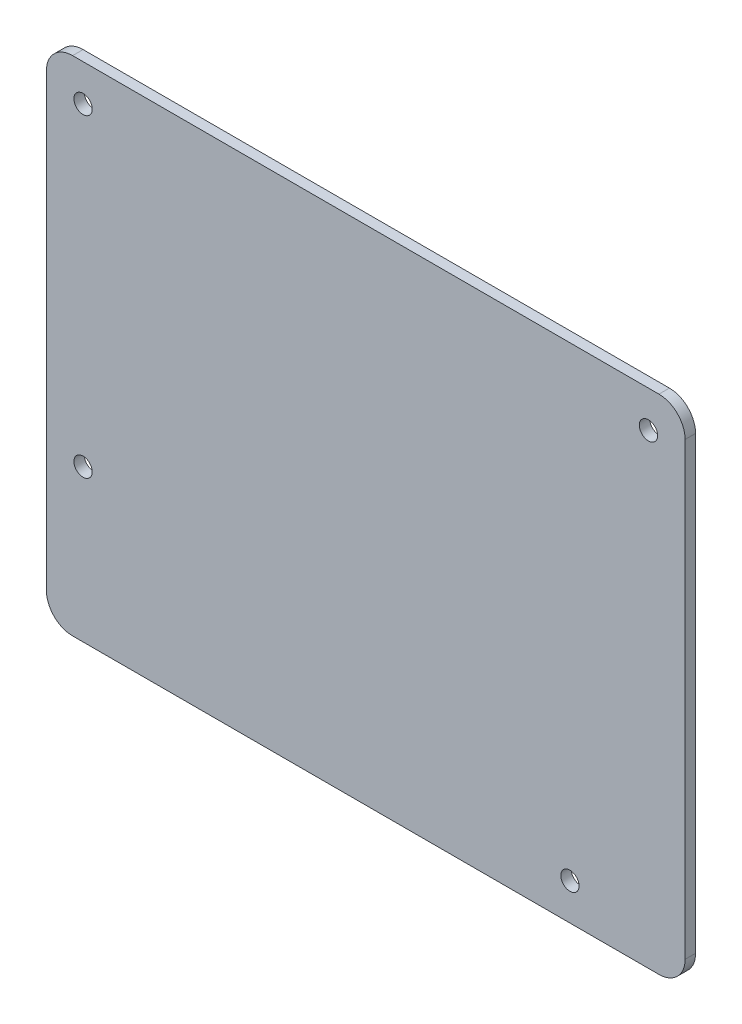
SolidWorks part; units mm, degrees
ref_plane "정면" through (0, 0, 0) normal (0, 0, 1) x (1, 0, 0)
ref_plane "윗면" through (0, 0, 0) normal (0, 1, 0) x (1, 0, 0)
ref_plane "우측면" through (0, 0, 0) normal (1, 0, 0) x (0, 0, -1)
sketch "Sketch1" plane through (0, 0, 0) normal (0, 0, 1) x (1, 0, 0)
  line L0 (-97, -4) -> (-97, 86) construction
  line L1 (22, 89) -> (-100, 89)
  line L2 (22, 89) -> (22, -7)
  line L3 (22, -7) -> (-100, -7)
  line L4 (-100, 89) -> (-100, -7)
  line L5 (22, 89) -> (-100, -7) construction
  line L6 (22, -7) -> (-100, 89) construction
  line L7 (-97, 86) -> (19, 86) construction
  line L8 (19, -4) -> (-97, -4) construction
  line L10 (19, 86) -> (19, -4) construction
  point P0 (-39, 41)
  dimension "D1" = 3
  dimension "D2" = 3
  dimension "D3" = 3
  dimension "D4" = 3
  dimension "D5" = 122
  dimension "D6" = 96
extrude "Boss-Extrude1" add sketch "Sketch1" along normal blind 2
hole_wizard "Ø3.5 (3.5) Diameter Hole1" positions "Sketch3" profile "Sketch2" hole size "Ø3.5" standard "ANSI Metric" end condition through all
sketch "Sketch3" plane through (0, 0, 2) normal (0, 0, 1) x (1, 0, 0)
  point P0 (0, 0)
  point P3 (15, 82)
  point P6 (-93, 82)
  point P9 (-93, 22)
sketch "Sketch2" plane through (0, 0, 2) normal (1, 0, 0) x (0, -1, 0)
  line L0 (0, 0) -> (0, 2)
  line L1 (0, 2) -> (1.75, 2)
  line L2 (1.75, 2) -> (1.75, 0)
  line L5 (1.75, 0) -> (0, 0)
  line L11 (0, -6.35) -> (0, 107.95) construction
  dimension "Thru Hole Dia." = 3.5
  dimension "Thru Hole Depth" = 2
fillet "Fillet1" radius 5 4 edges at (22, 89, 1) (-100, 89, 1) (-100, -7, 1) (22, -7, 1)
